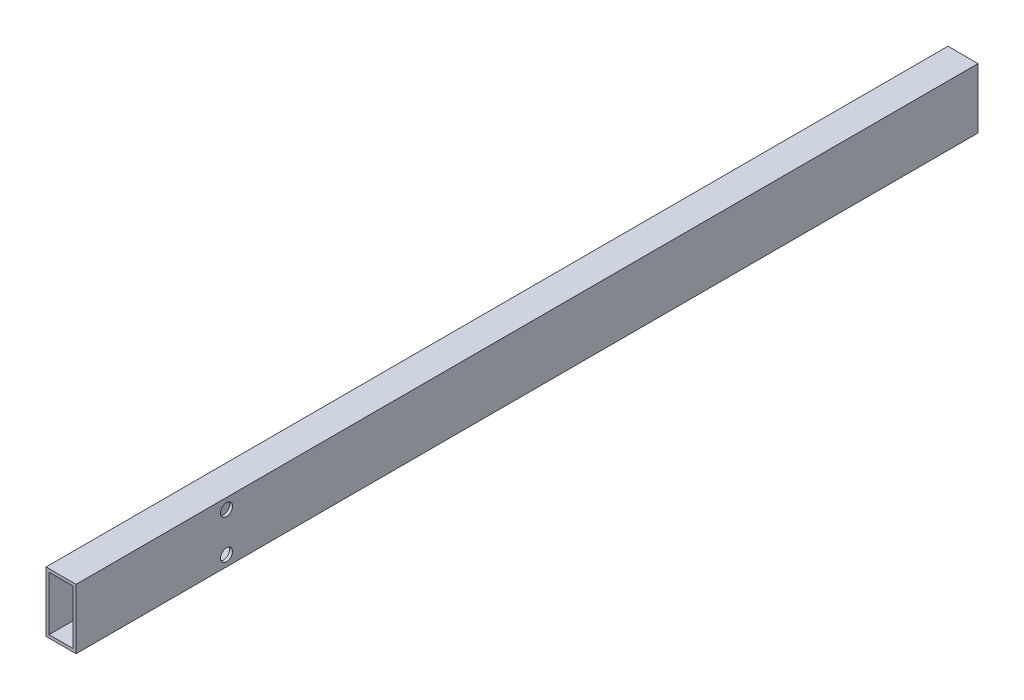
SolidWorks part; units mm, degrees
material "Hexcel AS4C (3000 Filaments)"
ref_plane "Ön Düzlem" through (0, 0, 0) normal (0, 0, 1) x (1, 0, 0)
ref_plane "Üst Düzlem" through (0, 0, 0) normal (0, 1, 0) x (1, 0, 0)
ref_plane "Sağ Düzlem" through (0, 0, 0) normal (1, 0, 0) x (0, 0, -1)
sketch "Çizim1" plane through (0, 0, 0) normal (0, 0, 1) x (1, 0, 0)
  line L1 (-5, 10) -> (5, 10)
  line L2 (-5, 10) -> (-5, -10)
  line L3 (-5, -10) -> (5, -10)
  line L4 (5, 10) -> (5, -10)
  line L5 (-5, 10) -> (5, -10) construction
  line L6 (-5, -10) -> (5, 10) construction
  point P0 (0, 0)
  dimension "D1" = 20
  dimension "D2" = 10
extrude "Yükseklik-Ekstrüzyon1" add sketch "Çizim1" along normal mid plane 300
shell "İç Boşaltma1" thickness 1
sketch "Çizim4" plane through (5, 0, 0) normal (1, 0, 0) x (0, 0, -1)
  circle A0 centre (-99.9552, 6.5) radius 2
  circle A1 centre (-99.9552, -6.5) radius 2
  dimension "D1" = 4
  dimension "D2" = 13
  dimension "D3" = 6.5
  dimension "D4" = 50.0448
extrude "Kes-Ekstrüzyon3" cut sketch "Çizim4" against normal blind 18
